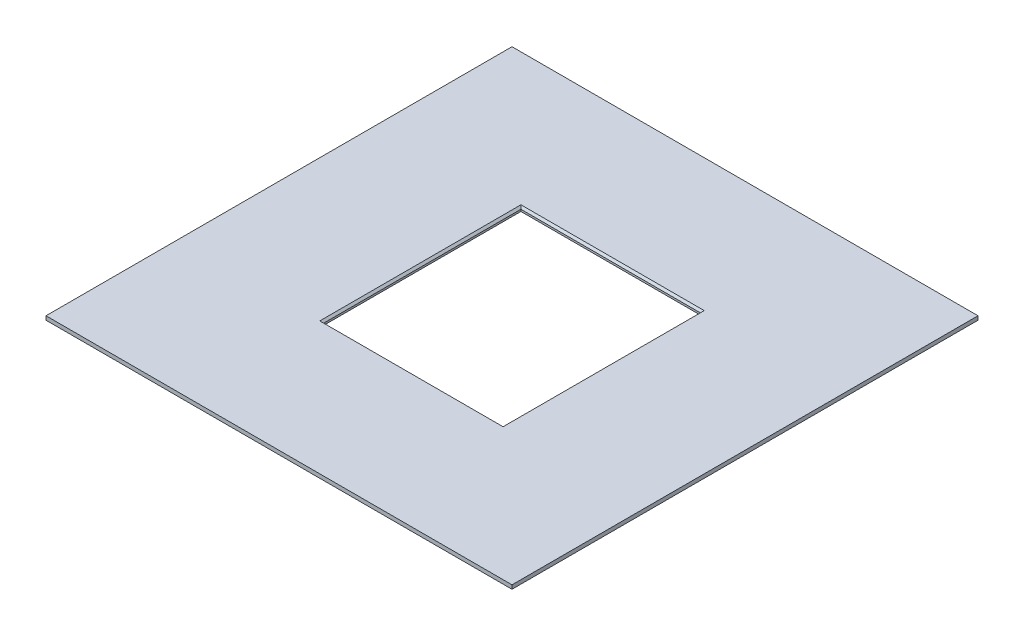
SolidWorks part; units mm, degrees
ref_plane "Front Plane" through (0, 0, 0) normal (0, 0, 1) x (1, 0, 0)
ref_plane "Top Plane" through (0, 0, 0) normal (0, 1, 0) x (1, 0, 0)
ref_plane "Right Plane" through (0, 0, 0) normal (1, 0, 0) x (0, 0, -1)
sketch "Sketch1" plane through (0, 0, 0) normal (0, 1, 0) x (1, 0, 0)
  line L1 (-60, 60) -> (60, 60)
  line L2 (-60, 60) -> (-60, -60)
  line L3 (-60, -60) -> (60, -60)
  line L4 (60, 60) -> (60, -60)
  line L5 (-60, 60) -> (60, -60) construction
  line L6 (-60, -60) -> (60, 60) construction
  line L11 (-23.9254, 23.9254) -> (24, -24) construction
  line L12 (-23.1, 25.4) -> (23.1, 25.4)
  line L13 (-23.1, 25.4) -> (-23.1, -25.4)
  line L14 (-23.1, -25.4) -> (23.1, -25.4)
  line L15 (23.1, 25.4) -> (23.1, -25.4)
  line L16 (-23.1, 25.4) -> (23.1, -25.4) construction
  line L17 (-23.1, -25.4) -> (23.1, 25.4) construction
  point P0 (0, 0)
  point P6 (0, 0)
  point P9 (0, 0)
  point P14 (0, 0)
  point P15 (0, 0)
  dimension "D1" = 120
  dimension "D2" = 120
  dimension "D3" = 46.2
  dimension "D4" = 50.8
extrude "Boss-Extrude1" add sketch "Sketch1" along normal blind 1
chamfer "Chamfer1" distance 0.5 angle 45 4 edges at (-23.1, 1, 0) (0, 1, 25.4) (23.1, 1, 0) (0, 1, -25.4)
